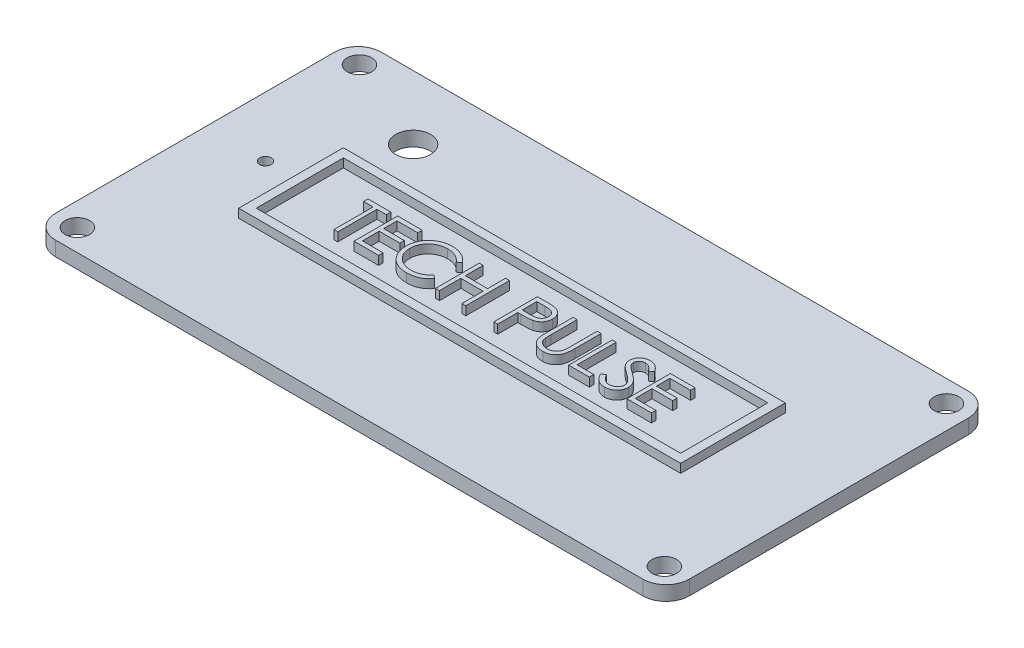
SolidWorks part; units mm, degrees
ref_plane "Front Plane" through (0, 0, 0) normal (0, 0, 1) x (1, 0, 0)
ref_plane "Top Plane" through (0, 0, 0) normal (0, 1, 0) x (1, 0, 0)
ref_plane "Right Plane" through (0, 0, 0) normal (1, 0, 0) x (0, 0, -1)
sketch "Sketch1" plane through (0, 0, 0) normal (0, 1, 0) x (1, 0, 0)
  line L1 (-54.5, 28) -> (54.5, 28)
  line L2 (-54.5, 28) -> (-54.5, -28)
  line L3 (-54.5, -28) -> (54.5, -28)
  line L4 (54.5, 28) -> (54.5, -28)
  dimension "D1" = 56
  dimension "D2" = 109
  dimension "D3" = 28
  dimension "D4" = 54.5
extrude "Top_Plate" add sketch "Sketch1" along normal blind 2.5
fillet "Fillet2" radius 4 4 edges at (-54.5, 1.25, -28) (-54.5, 1.25, 28) (54.5, 1.25, -28) (54.5, 1.25, 28)
sketch "Sketch7" plane through (0, 2.5, 0) normal (0, 1, 0) x (1, 0, 0)
  line L2 (-54.5, 24) -> (-54.5, -24) construction
  line L3 (50.5, 28) -> (-50.5, 28) construction
  circle A0 centre (-34, 17) radius 3
  dimension "D2" = 6
  dimension "D3" = 20.5
  dimension "D4" = 11
extrude "Cut-Extrude3" cut sketch "Sketch7" against normal blind 5
sketch "Sketch11" plane through (0, 2.5, 0) normal (0, 1, 0) x (1, 0, 0)
  arc A0 (54.5, 24) -> (50.5, 28) centre (50.5, 24) ccw construction
  arc A1 (50.5, -28) -> (54.5, -24) centre (50.5, -24) ccw construction
  circle A2 centre (-50.4771, 24.2414) radius 2.1
  circle A3 centre (-50.4925, -24.2586) radius 2.1
  circle A4 centre (50.4617, -24.2586) radius 2.1
  circle A5 centre (50.4771, 24.2414) radius 2.1
  arc A6 (-50.5, 28) -> (-54.5, 24) centre (-50.5, 24) ccw construction
  arc A8 (-54.5, -24) -> (-50.5, -28) centre (-50.5, -24) ccw construction
  point P7 (53.3284, 26.8284)
  point P11 (53.3284, -26.8284)
  point P13 (-53.3284, 26.8284)
  point P23 (-53.3284, -26.8284)
  point P24 (0, 0)
  point P25 (0, 0)
  point P26 (0, 0)
  point P27 (0, 0)
  dimension "D5" = 4.2
  dimension "D4" = 3.85
  dimension "D1" = 3.85
  dimension "D2" = 3.8271
  dimension "D3" = 3.85
  dimension "D8" = 48.5
  dimension "D6" = 2
  dimension "D7" = 2
extrude "Cut-Extrude5" cut sketch "Sketch11" against normal blind 4
sketch "Sketch12" plane through (0, 2.5, 0) normal (0, 1, 0) x (1, 0, 0)
  line L1 (38, 9) -> (-38, 9)
  line L2 (38, 9) -> (38, -9)
  line L3 (38, -9) -> (-38, -9)
  line L4 (-38, 9) -> (-38, -9)
  dimension "D3" = 76
  dimension "D1" = 18
  dimension "D2" = 9
  dimension "D4" = 38
extrude "Boss-Extrude1" add sketch "Sketch12" along normal blind 1.5
sketch "Sketch13" plane through (0, 4, 0) normal (0, 1, 0) x (1, 0, 0)
  line L0 (38, 9) -> (-38, 9) construction
  line L1 (36.5, 7.5) -> (-36.5, 7.5)
  line L2 (36.5, 7.5) -> (36.5, -7.5)
  line L3 (36.5, -7.5) -> (-36.5, -7.5)
  line L4 (-36.5, 7.5) -> (-36.5, -7.5)
  line L5 (-38, -9) -> (38, -9) construction
  line L6 (38, -9) -> (38, 9) construction
  line L7 (-38, 9) -> (-38, -9) construction
  dimension "D1" = 1.5
  dimension "D2" = 1.5
  dimension "D3" = 1.5
  dimension "D4" = 1.5
extrude "Cut-Extrude6" cut sketch "Sketch13" against normal blind 1.5
sketch "Sketch14" plane through (0, 2.5, 0) normal (0, 1, 0) x (1, 0, 0)
  line L0 (-36.5, -4) -> (36.5, -4) construction
  line L1 (-36.5, 7.5) -> (-36.5, -7.5) construction
  line L2 (36.5, -7.5) -> (36.5, 7.5) construction
  text T0 "TECH PULSE" font "Century Gothic" height 7.5
  dimension "D1" = 4
  dimension "D2" = 4
extrude "Boss-Extrude2" add sketch "Sketch14" along normal blind 1.5
sketch "Sketch15" plane through (0, 2.5, 0) normal (0, 1, 0) x (1, 0, 0)
  line L0 (50.5, 28) -> (-50.5, 28) construction
  line L1 (-54.5, 24) -> (-54.5, -24) construction
  circle A0 centre (-44.2, 1.8) radius 1
  dimension "D1" = 2
  dimension "D2" = 26.2
  dimension "D3" = 10.3
extrude "Cut-Extrude7" cut sketch "Sketch15" against normal blind 3
